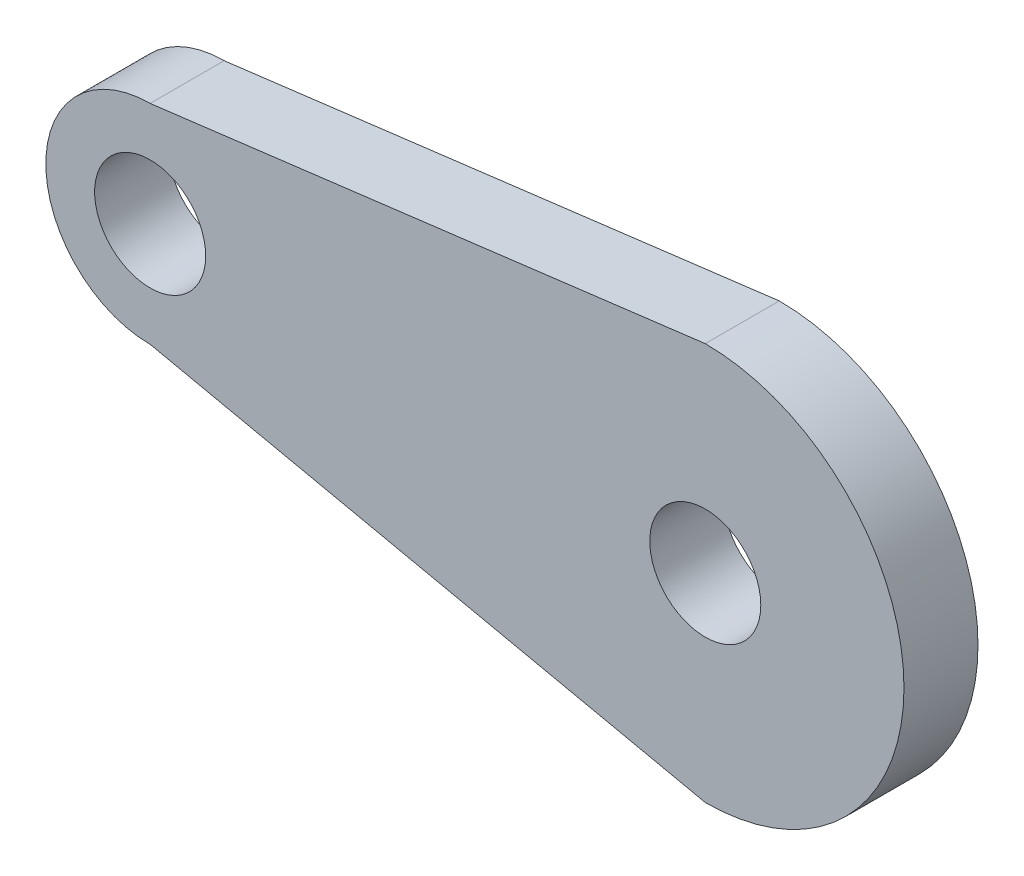
SolidWorks part; units mm, degrees
ref_plane "Front Plane" through (0, 0, 0) normal (0, 0, 1) x (1, 0, 0)
ref_plane "Top Plane" through (0, 0, 0) normal (0, 1, 0) x (1, 0, 0)
ref_plane "Right Plane" through (0, 0, 0) normal (1, 0, 0) x (0, 0, -1)
sketch "Sketch1" plane through (0, 0, 0) normal (0, 0, 1) x (1, 0, 0)
  line L0 (0, 0) -> (15, 1.8792)
  line L1 (0, -5.6376) -> (15, -8.8591)
  line L2 (0, 0) -> (0, -5.6376)
  line L3 (15, 1.8792) -> (15, -8.8591)
  line L4 (0, -2.8188) -> (15, -3.4899)
  arc A0 (0, 0) -> (0, -5.6376) centre (0, -2.8188) ccw
  arc A1 (15, 1.8792) -> (15, -8.8591) centre (15, -3.4899) cw
  circle A2 centre (0, -2.8188) radius 1.5
  circle A3 centre (15, -3.4899) radius 1.5
  dimension "D1" = 15
extrude "Boss-Extrude1" add sketch "Sketch1" along normal blind 2 contours A3 L3 L0 L2 A2 L4 | A3 L4 A2 L2 L1 L3 | A3 L3 A1 | A2 L2 A0
